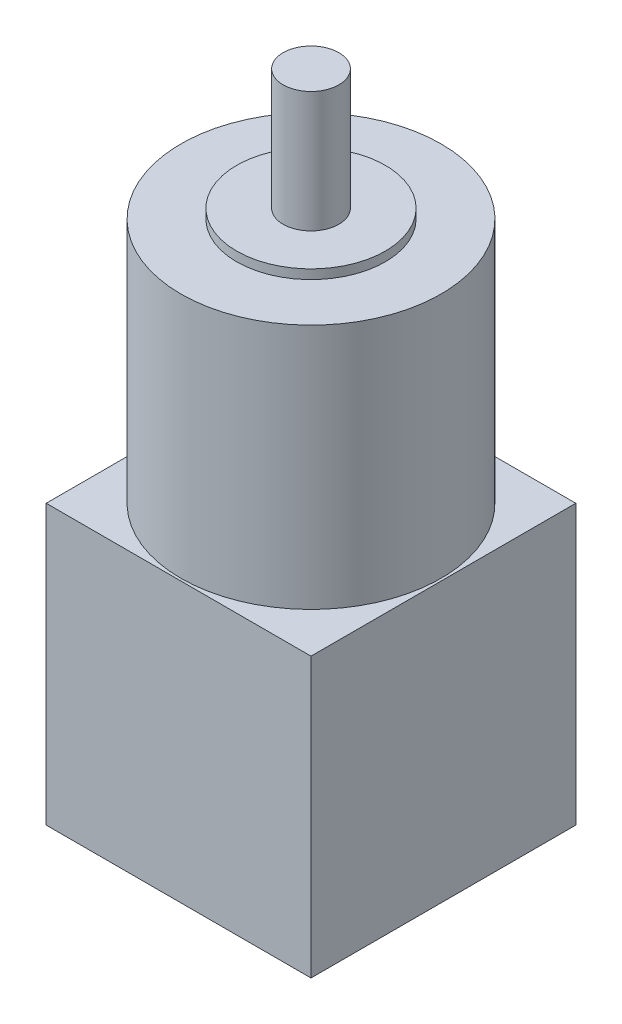
SolidWorks part; units mm, degrees
ref_plane "Front Plane" through (0, 0, 0) normal (0, 0, 1) x (1, 0, 0)
ref_plane "Top Plane" through (0, 0, 0) normal (0, 1, 0) x (1, 0, 0)
ref_plane "Right Plane" through (0, 0, 0) normal (1, 0, 0) x (0, 0, -1)
sketch "Sketch1" plane through (0, 0, 0) normal (0, 1, 0) x (1, 0, 0)
  circle A0 centre (0, 0) radius 28
  dimension "D1" = 56
extrude "Boss-Extrude1" add sketch "Sketch1" along normal blind 53
sketch "Sketch2" plane through (0, 53, 0) normal (0, 1, 0) x (1, 0, 0)
  circle A0 centre (0, 0) radius 16
  dimension "D1" = 32
extrude "Boss-Extrude2" add sketch "Sketch2" along normal blind 2
sketch "Sketch3" plane through (0, 55, 0) normal (0, 1, 0) x (1, 0, 0)
  circle A0 centre (0, 0) radius 6
  dimension "D1" = 12
extrude "Boss-Extrude3" add sketch "Sketch3" along normal blind 26
sketch "Sketch4" plane through (0, 0, 0) normal (0, -1, 0) x (1, 0, 0)
  line L1 (-28.5, -28.5) -> (28.5, -28.5)
  line L2 (-28.5, -28.5) -> (-28.5, 28.5)
  line L3 (-28.5, 28.5) -> (28.5, 28.5)
  line L4 (28.5, -28.5) -> (28.5, 28.5)
  line L5 (-28.5, -28.5) -> (28.5, 28.5) construction
  line L6 (-28.5, 28.5) -> (28.5, -28.5) construction
  point P0 (0, 0)
  dimension "D1" = 57
extrude "Boss-Extrude4" add sketch "Sketch4" along normal blind 60
